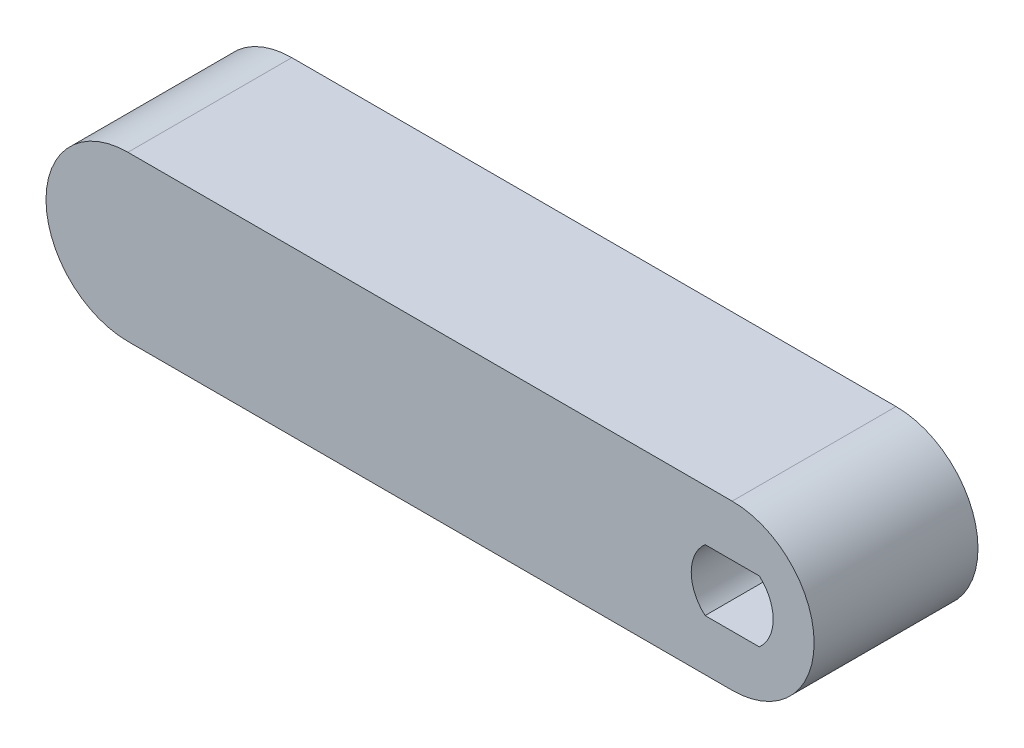
SolidWorks part; units mm, degrees
ref_plane "Front Plane" through (0, 0, 0) normal (0, 0, 1) x (1, 0, 0)
ref_plane "Top Plane" through (0, 0, 0) normal (0, 1, 0) x (1, 0, 0)
ref_plane "Right Plane" through (0, 0, 0) normal (1, 0, 0) x (0, 0, -1)
sketch "Sketch1" plane through (0, 0, 0) normal (0, 0, 1) x (1, 0, 0)
  line L0 (0, 8) -> (-59, 8)
  line L1 (-59, -8) -> (0, -8)
  line L2 (0, 3) -> (0, 4) construction
  line L3 (2.6458, 3) -> (-2.6458, 3)
  line L4 (2.6458, 3) -> (2.6458, -3)
  line L5 (2.6458, -3) -> (-2.6458, -3)
  line L6 (-2.6458, 3) -> (-2.6458, -3)
  line L7 (2.6458, 3) -> (-2.6458, -3) construction
  line L8 (2.6458, -3) -> (-2.6458, 3) construction
  line L9 (-67, 0) -> (8, 0) construction
  circle A0 centre (0, 0) radius 8
  circle A1 centre (-59, 0) radius 8
  circle A2 centre (0, 0) radius 4
  dimension "D2" = 8
  dimension "D3" = 16
  dimension "D1" = 1
  dimension "D4" = 75
extrude "Boss-Extrude1" add sketch "Sketch1" against normal blind 16 contours A1 | A1 L1 A0 L0 | A0 A2 | L3 A2 | L5 A2
